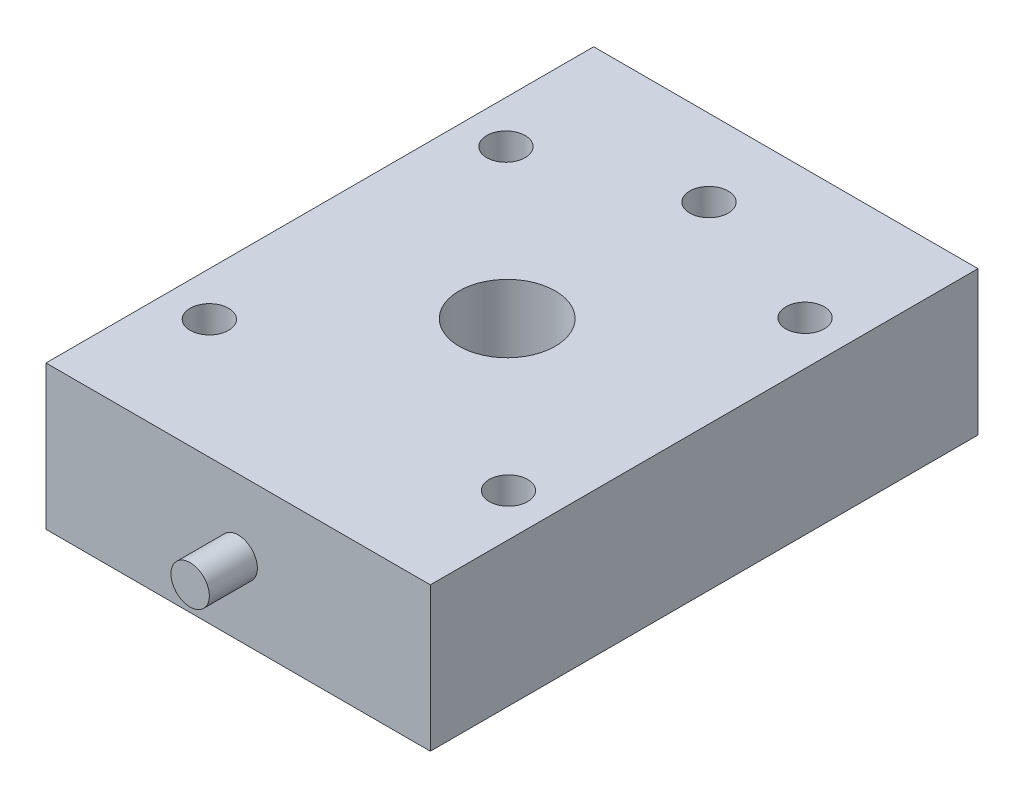
SolidWorks part; units mm, degrees
ref_plane "Front Plane" through (0, 0, 0) normal (0, 0, 1) x (1, 0, 0)
ref_plane "Top Plane" through (0, 0, 0) normal (0, 1, 0) x (1, 0, 0)
ref_plane "Right Plane" through (0, 0, 0) normal (1, 0, 0) x (0, 0, -1)
sketch "Sketch1" plane through (0, 0, 0) normal (0, 0, 1) x (1, 0, 0)
  line L1 (-20, -7.5) -> (20, -7.5)
  line L2 (-20, -7.5) -> (-20, 7.5)
  line L3 (-20, 7.5) -> (20, 7.5)
  line L4 (20, -7.5) -> (20, 7.5)
  line L5 (-20, -7.5) -> (20, 7.5) construction
  line L6 (-20, 7.5) -> (20, -7.5) construction
  point P0 (0, 0)
  dimension "D1" = 15
  dimension "D2" = 40
extrude "Boss-Extrude1" add sketch "Sketch1" along normal blind 57
sketch "Sketch2" plane through (0, 0, 57) normal (0, 0, 1) x (1, 0, 0)
  circle A0 centre (0, 0) radius 2
  dimension "D1" = 4
extrude "Boss-Extrude2" add sketch "Sketch2" along normal blind 5
sketch "Sketch3" plane through (0, 0, 0) normal (0, 0, -1) x (-1, 0, 0)
  circle A0 centre (0, 0) radius 2.5
  dimension "D1" = 5
extrude "Cut-Extrude1" cut sketch "Sketch3" against normal blind 23
sketch "Sketch5" plane through (0, 7.5, 0) normal (0, 1, 0) x (1, 0, 0)
  line L0 (0, 0) -> (0, -57) construction
  line L1 (20, 0) -> (-20, 0) construction
  line L2 (20, -57) -> (-20, -57) construction
  circle A0 centre (0, -8) radius 2
  dimension "D1" = 4
  dimension "D2" = 8
extrude "Cut-Extrude3" cut sketch "Sketch5" against normal blind 8
sketch "Sketch7" plane through (0, -7.5, 0) normal (0, -1, 0) x (-1, 0, 0)
  line L0 (-78, -29) -> (0, -29) construction
  line L2 (0, -1057) -> (0, 48943) construction
  line L3 (20, -57) -> (-20, -57) construction
  circle A0 centre (0, -29) radius 5
  point P8 (0, -57)
  dimension "D1" = 10
extrude "Cut-Extrude5" cut sketch "Sketch7" against normal through all
sketch "Sketch8" plane through (0, -7.5, 0) normal (0, -1, 0) x (-1, 0, 0)
  circle A0 centre (-15.4335, -13.4337) radius 2
  circle A1 centre (-15.5663, -44.4335) radius 2
  circle A2 centre (15.4335, -44.5663) radius 2
  circle A3 centre (15.5663, -13.5665) radius 2
extrude "Cut-Extrude6" cut sketch "Sketch8" against normal blind 29
